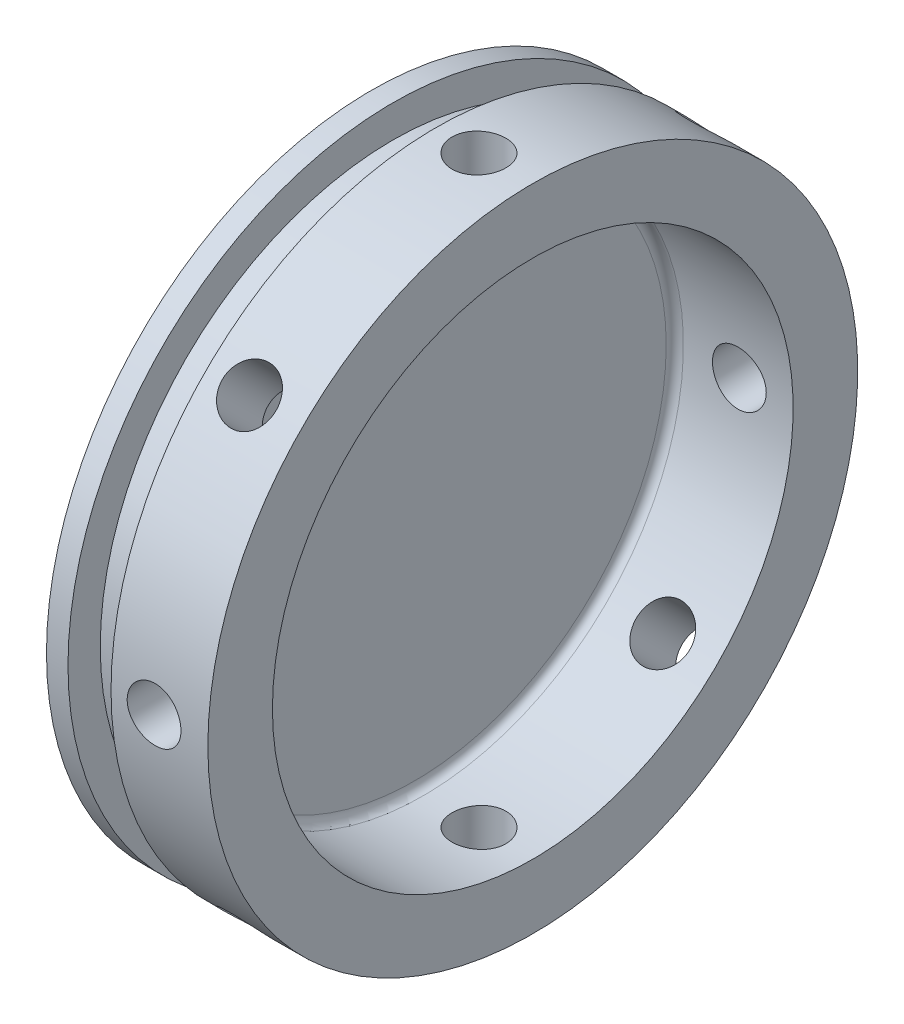
SolidWorks part; units mm, degrees
ref_plane "Front" through (0, 0, 0) normal (0, 0, 1) x (1, 0, 0)
ref_plane "Top" through (0, 0, 0) normal (0, 1, 0) x (1, 0, 0)
ref_plane "Right" through (0, 0, 0) normal (1, 0, 0) x (0, 0, -1)
sketch "Sketch1" plane through (0, 0, 0) normal (0, 1, 0) x (1, 0, 0)
  line L0 (0, 0) -> (43.6365, 0) construction
  line L1 (0, 0) -> (0, 30.2)
  line L2 (15, 30.2) -> (15, 24.2)
  line L3 (15, 24.2) -> (4, 24.2)
  line L4 (4, 24.2) -> (4, 0)
  line L5 (4, 0) -> (0, 0)
  line L6 (0, 30.2) -> (2, 30.2)
  line L7 (2, 30.2) -> (2, 27.2)
  line L8 (2, 27.2) -> (6, 27.2)
  line L9 (6, 27.2) -> (6, 30.2)
  line L10 (6, 30.2) -> (15, 30.2)
  dimension "D1" = 30.2
  dimension "D2" = 4
  dimension "D3" = 6
  dimension "D4" = 15
  dimension "D5" = 2
  dimension "D6" = 4
  dimension "D7" = 3
revolve "Revolve1" add sketch "Sketch1" angle 360 about L0
sketch "Sketch2" plane through (0, 0, 0) normal (0, 1, 0) x (1, 0, 0)
  circle A0 centre (10, 0) radius 2.5
  dimension "D1" = 5
  dimension "D2" = 10
extrude "Cut-Extrude1" cut sketch "Sketch2" against normal blind 100
ref_axis "Axis1" through (4, 0, 0) along (1, 0, 0)
pattern_circular "CirPattern1" count 8 over 360 about axis through (4, 0, 0) along (1, 0, 0) of "Cut-Extrude1"
fillet "Fillet1" radius 0.8 1 edges at (4, 0, 24.2)
